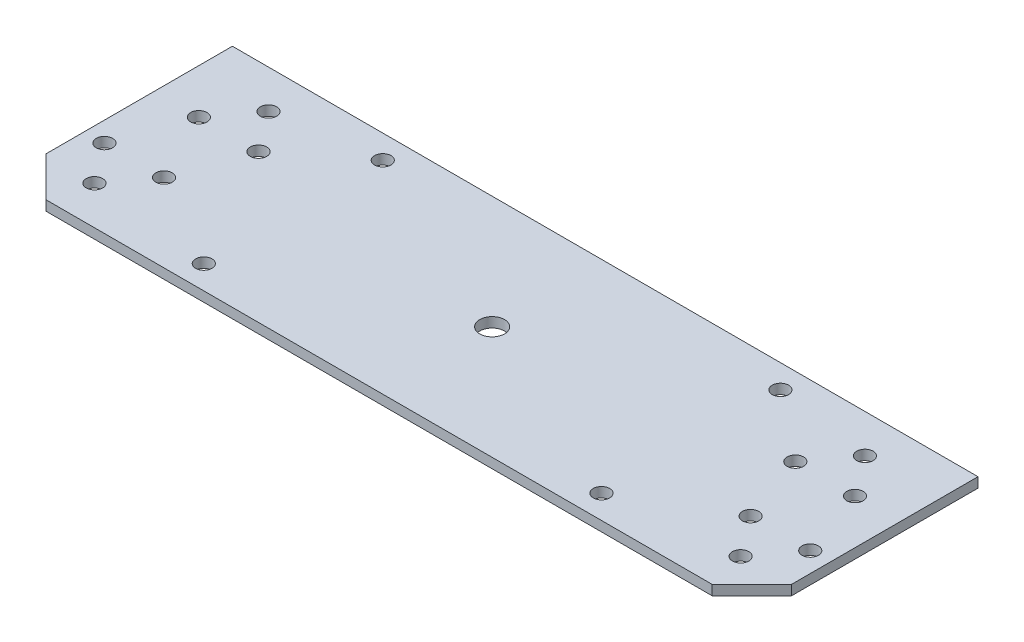
SolidWorks part; units mm, degrees
ref_plane "前视基准面" through (0, 0, 0) normal (0, 0, 1) x (1, 0, 0)
ref_plane "上视基准面" through (0, 0, 0) normal (0, 1, 0) x (1, 0, 0)
ref_plane "右视基准面" through (0, 0, 0) normal (1, 0, 0) x (0, 0, -1)
sketch "草图1" plane through (0, 0, 0) normal (0, 1, 0) x (1, 0, 0)
  line L1 (-75, -22.75) -> (75, -22.75)
  line L2 (-75, -22.75) -> (-75, 22.75)
  line L3 (-75, 22.75) -> (75, 22.75)
  line L4 (75, -22.75) -> (75, 22.75)
  line L5 (-75, -22.75) -> (75, 22.75) construction
  line L6 (-75, 22.75) -> (75, -22.75) construction
  point P0 (0, 0)
  dimension "D1" = 45.5
  dimension "D2" = 150
extrude "凸台-拉伸1" add sketch "草图1" along normal blind 2
sketch "草图2" plane through (0, 2, 0) normal (0, 1, 0) x (1, 0, 0)
  line L0 (-60, -11) -> (-65, -11) construction
  line L1 (-60, -11) -> (60, -11) construction
  line L2 (-60, -11) -> (-60, 11) construction
  line L3 (-60, 11) -> (60, 11) construction
  line L4 (60, -11) -> (60, 11) construction
  line L5 (-60, -11) -> (60, 11) construction
  line L6 (-60, 11) -> (60, -11) construction
  line L12 (-66, 7) -> (-54, 7) construction
  line L13 (-71, -15) -> (-59, -15) construction
  line L14 (-66, 7) -> (-66, 15) construction
  line L15 (-66, 15) -> (-54, 15) construction
  line L16 (-54, 7) -> (-54, 15) construction
  line L17 (-66, 7) -> (-54, 15) construction
  line L18 (-66, 15) -> (-54, 7) construction
  line L19 (-71, -15) -> (-71, -7) construction
  line L20 (-71, -7) -> (-59, -7) construction
  line L21 (-59, -15) -> (-59, -7) construction
  line L22 (-71, -15) -> (-59, -7) construction
  line L23 (-71, -7) -> (-59, -15) construction
  circle A4 centre (-60, 15) radius 1.65
  circle A5 centre (-66, 7) radius 1.65
  circle A6 centre (-54, 7) radius 1.65
  circle A7 centre (-71, -7) radius 1.65
  circle A8 centre (-59, -7) radius 1.65
  circle A9 centre (-65, -15) radius 1.65
  point P0 (0, 0)
  point P14 (-60, 0)
  dimension "D5" = 3.3
  dimension "D1" = 12
  dimension "D2" = 8
  dimension "D3" = 15
  dimension "D4" = 120
  dimension "D6" = 5
  dimension "D7" = 8
  dimension "D8" = 12
extrude "切除-拉伸1" cut sketch "草图2" against normal up to next
mirror "镜向1" about plane through (0, 0, 0) normal (1, 0, 0) of "切除-拉伸1"
chamfer "倒角1" distance 8 angle 45 2 edges at (75, 1, 22.75) (-75, 1, 22.75)
sketch "草图3" plane through (0, 2, 0) normal (0, 1, 0) x (1, 0, 0)
  circle A0 centre (0, 0) radius 2.5
  dimension "D1" = 5
extrude "临时配合孔" cut sketch "草图3" against normal up to next
sketch "草图4" plane through (0, 2, 0) normal (0, 1, 0) x (1, 0, 0)
  line L1 (-40, -18) -> (40, -18) construction
  line L2 (-40, -18) -> (-40, 18) construction
  line L3 (-40, 18) -> (40, 18) construction
  line L4 (40, -18) -> (40, 18) construction
  line L5 (-40, -18) -> (40, 18) construction
  line L6 (-40, 18) -> (40, -18) construction
  circle A0 centre (-40, 18) radius 1.65
  circle A1 centre (-40, -18) radius 1.65
  circle A2 centre (40, 18) radius 1.65
  circle A3 centre (40, -18) radius 1.65
  point P0 (0, 0)
  dimension "D3" = 3.3
  dimension "D1" = 36
  dimension "D2" = 80
extrude "切除-拉伸2" cut sketch "草图4" against normal up to next
